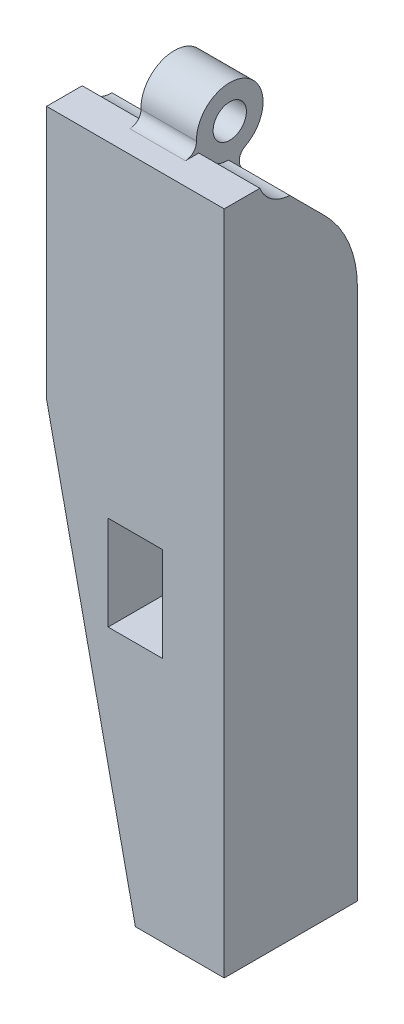
SolidWorks part; units mm, degrees
ref_plane "Front Plane" through (0, 0, 0) normal (0, 0, 1) x (1, 0, 0)
ref_plane "Top Plane" through (0, 0, 0) normal (0, 1, 0) x (1, 0, 0)
ref_plane "Right Plane" through (0, 0, 0) normal (1, 0, 0) x (0, 0, -1)
sketch "Sketch1" plane through (0, 0, 0) normal (0, 0, 1) x (1, 0, 0)
  line L0 (-8, 0) -> (8, 0)
  line L1 (8, 0) -> (8, -60)
  line L2 (-8, 0) -> (-8, -60)
  line L3 (-8, -60) -> (8, -60)
  point P4 (0, 0)
extrude "Boss-Extrude1" add sketch "Sketch1" along normal blind 12
sketch "Sketch2" plane through (0, 0, 0) normal (1, 0, 0) x (0, 0, -1)
  line L0 (-12, 0) -> (-8, 0)
  line L1 (-12, 0) -> (0, 0) construction
  line L2 (0, -60) -> (0, 0) construction
  line L3 (-8, 0) -> (0, 0)
  line L6 (0, 0) -> (0, -8)
  line L7 (-8, 0) -> (0, -8)
extrude "Cut-Extrude1" cut sketch "Sketch2" against normal through all both and the other way through all contours L3 L6 L7
sketch "Sketch3" plane through (0, 0, 0) normal (1, 0, 0) x (0, 0, -1)
  line L0 (-12, 0) -> (0, 0)
  line L1 (-6, 0) -> (-6, 1.1)
  circle A0 centre (-6, 1.1) radius 1.5
  circle A1 centre (-6, 1.1) radius 3
extrude "Cut-Extrude3" cut sketch "Sketch3" against normal through all both and the other way through all contours L0 A1 A0 | L0 A1 A0
sketch "Sketch4" plane through (0, 0, 0) normal (1, 0, 0) x (0, 0, -1)
  circle A0 centre (-6, 1.1) radius 1.5
  circle A1 centre (-6, 1.1) radius 3
extrude "Boss-Extrude2" add sketch "Sketch4" along normal mid plane 5
fillet "Fillet1" radius 1 2 edges at (0, 0, 8.7911) (0, -1.8983, 6.1017)
sketch "Sketch5" plane through (0, 0, 0) normal (0, 0, -1) x (-1, 0, 0)
  line L0 (0, -60) -> (8, -22.8516)
  line L1 (8, -60) -> (-8, -60) construction
  line L2 (8, -8) -> (8, -60) construction
  line L3 (0, -60) -> (8, -60)
  line L4 (8, -60) -> (8, -22.8516)
extrude "Cut-Extrude4" cut sketch "Sketch5" against normal through all
fillet "Fillet2" radius 10 1 edges at (0, -8, 0)
sketch "Sketch6" plane through (0, 0, 0) normal (0, 0, -1) x (-1, 0, 0)
  line L0 (8, -22.8516) -> (-8, -22.8516)
  line L1 (-8, -60) -> (-8, -12.1421) construction
  line L2 (8, -12.1421) -> (-8, -12.1421) construction
  line L3 (-2.4566, -20.4574) -> (2.4566, -20.4574)
  line L4 (-2.4566, -20.4574) -> (-2.4566, -29.3581)
  line L5 (-2.4566, -29.3581) -> (2.4566, -29.3581)
  line L6 (2.4566, -20.4574) -> (2.4566, -29.3581)
  line L9 (-2.4566, -29.3581) -> (2.4566, -29.3581)
  line L10 (-2.4566, -29.3581) -> (-2.4566, -37.8516)
  line L11 (-2.4566, -37.8516) -> (2.4566, -37.8516)
  line L12 (2.4566, -29.3581) -> (2.4566, -37.8516)
  line L13 (2.4566, -20.4574) -> (-2.4566, -20.4574)
  line L14 (2.4566, -20.4574) -> (2.4566, -12.1421)
  line L15 (2.4566, -12.1421) -> (-2.4566, -12.1421)
  line L16 (-2.4566, -20.4574) -> (-2.4566, -12.1421)
  point P5 (0, -22.8516)
  line M14 (8, -12.1421) -> (-8, -12.1421)
extrude "Cut-Extrude5" cut sketch "Sketch6" against normal blind 5 contours L16 L3 L14 M14 | L12 L5 L10 L11
sketch "Sketch7" plane through (0, 0, 0) normal (0, 0, -1) x (-1, 0, 0)
  line L1 (-2.4566, -29.3581) -> (2.4566, -29.3581)
  line L2 (-2.4566, -29.3581) -> (-2.4566, -37.8516)
  line L3 (-2.4566, -37.8516) -> (2.4566, -37.8516)
  line L4 (2.4566, -29.3581) -> (2.4566, -37.8516)
extrude "Cut-Extrude6" cut sketch "Sketch7" against normal through all
sketch "Sketch8" plane through (0, -20.4574, 0) normal (0, 1, 0) x (1, 0, 0)
  line L0 (-2.4566, -5) -> (-2.4566, 0) construction
  line L1 (2.4566, -5) -> (-2.4566, -5)
  line L2 (2.4566, -5) -> (2.4566, -2.5)
  line L3 (2.4566, -2.5) -> (-2.4566, -2.5)
  line L4 (-2.4566, -5) -> (-2.4566, -2.5)
extrude "Cut-Extrude7" cut sketch "Sketch8" against normal up to next
